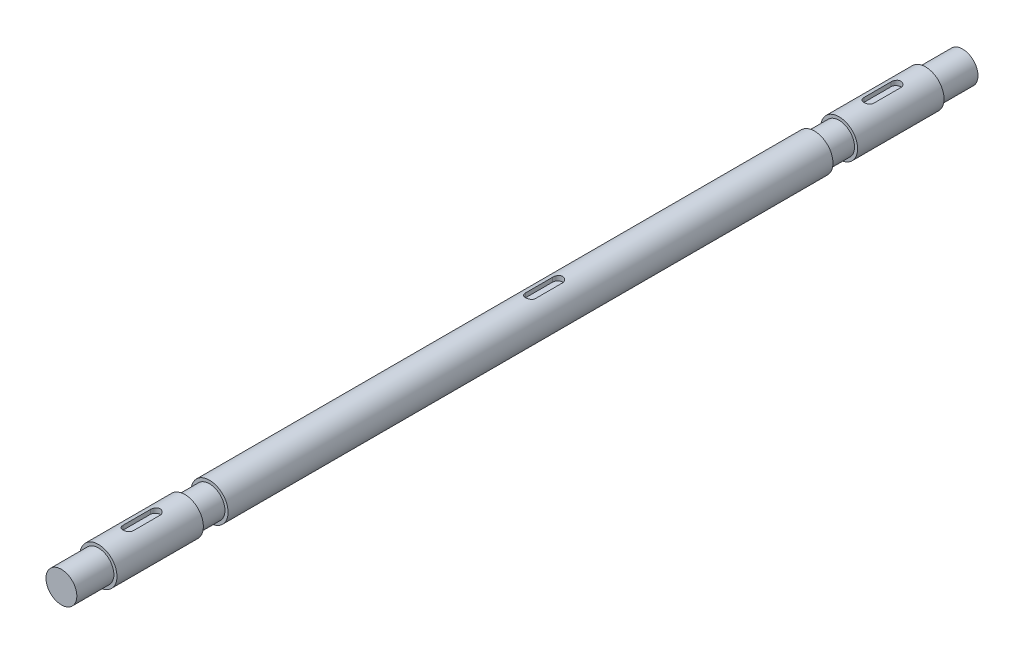
SolidWorks part; units mm, degrees
ref_plane "Front" through (0, 0, 0) normal (0, 0, 1) x (1, 0, 0)
ref_plane "Top" through (0, 0, 0) normal (0, 1, 0) x (1, 0, 0)
ref_plane "Right" through (0, 0, 0) normal (1, 0, 0) x (0, 0, -1)
sketch "Sketch1" plane through (0, 0, 0) normal (1, 0, 0) x (0, 0, -1)
  line L0 (-91.7234, 0) -> (762.5474, 0) construction
  line L1 (0, 15) -> (70, 15)
  line L2 (-30, 12.5) -> (-30, 0)
  line L3 (-30, 0) -> (700, 0)
  line L4 (700, 12.5) -> (700, 0)
  line L5 (70, 15) -> (70, 12.5)
  line L6 (-30, 12.5) -> (0, 12.5)
  line L7 (0, 12.5) -> (0, 15)
  line L8 (70, 12.5) -> (90, 12.5)
  line L9 (90, 12.5) -> (90, 15)
  line L10 (90, 15) -> (580, 15)
  line L11 (580, 15) -> (580, 12.5)
  line L12 (580, 12.5) -> (600, 12.5)
  line L13 (600, 12.5) -> (600, 15)
  line L14 (600, 15) -> (670, 15)
  line L15 (670, 15) -> (670, 12.5)
  line L16 (670, 12.5) -> (700, 12.5)
  dimension "D1" = 30
  dimension "D2" = 600
  dimension "D3" = 30
  dimension "D4" = 25
  dimension "D5" = 70
  dimension "D6" = 90
  dimension "D7" = 580
  dimension "D8" = 670
  dimension "D9" = 700
revolve "Revolve1" add sketch "Sketch1" angle 360 about L0
sketch "Sketch2" plane through (0, 0, 0) normal (0, 1, 0) x (1, 0, 0)
  line L0 (0, 646) -> (0, 624) construction
  line L1 (4, 646) -> (4, 624)
  line L2 (-4, 646) -> (-4, 624)
  line L3 (0, 372) -> (0, 350) construction
  line L4 (4, 372) -> (4, 350)
  line L5 (-4, 372) -> (-4, 350)
  line L6 (0, 46) -> (0, 24) construction
  line L7 (4, 46) -> (4, 24)
  line L8 (-4, 46) -> (-4, 24)
  line L10 (-12.5, 0) -> (12.5, 0) construction
  arc A0 (4, 646) -> (-4, 646) centre (0, 646) ccw
  arc A1 (-4, 624) -> (4, 624) centre (0, 624) ccw
  arc A2 (4, 372) -> (-4, 372) centre (0, 372) ccw
  arc A3 (-4, 350) -> (4, 350) centre (0, 350) ccw
  arc A4 (4, 46) -> (-4, 46) centre (0, 46) ccw
  arc A5 (-4, 24) -> (4, 24) centre (0, 24) ccw
  point P2 (0, 635)
  point P7 (0, 361)
  point P14 (0, 35)
  dimension "D1" = 22
  dimension "D2" = 8
  dimension "D3" = 35
  dimension "D4" = 326
  dimension "D5" = 274
extrude "Cut-Extrude1" cut sketch "Sketch2" along normal through all from offset 11
